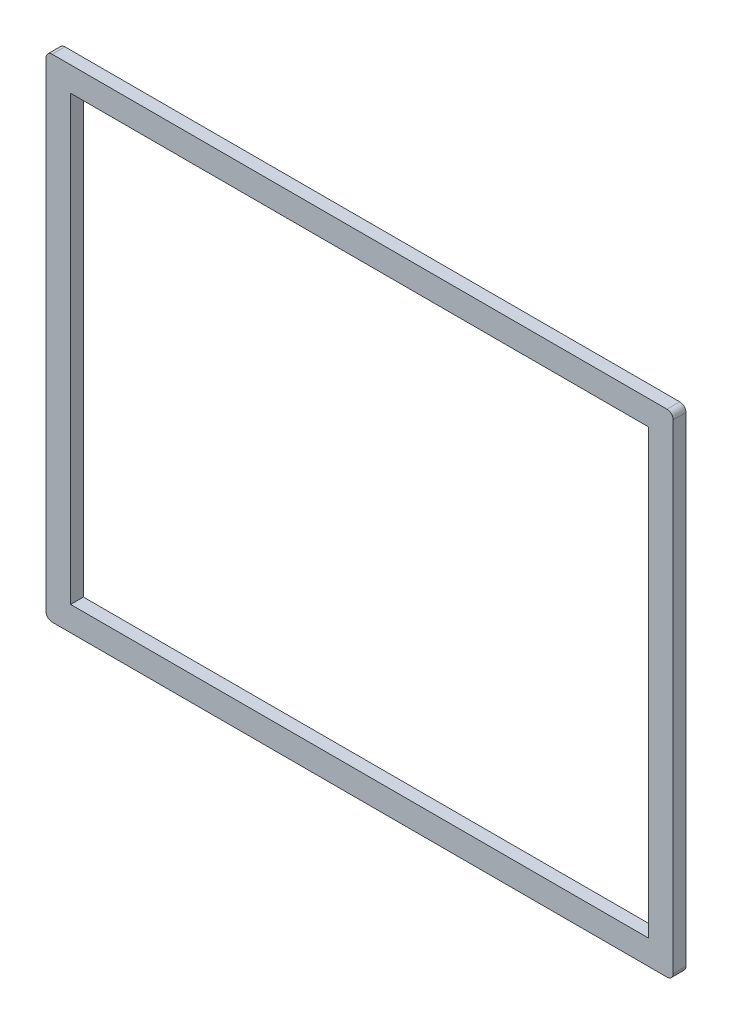
SolidWorks part; units mm, degrees
ref_plane "Front Plane" through (0, 0, 0) normal (0, 0, 1) x (1, 0, 0)
ref_plane "Top Plane" through (0, 0, 0) normal (0, 1, 0) x (1, 0, 0)
ref_plane "Right Plane" through (0, 0, 0) normal (1, 0, 0) x (0, 0, -1)
sketch "Sketch1" plane through (0, 0, 0) normal (0, 0, 1) x (1, 0, 0)
  line L0 (-298.45, -228.6) -> (298.45, 228.6) construction
  line L1 (-298.45, 228.6) -> (298.45, 228.6)
  line L2 (-298.45, 228.6) -> (-298.45, -228.6)
  line L3 (-298.45, -228.6) -> (298.45, -228.6)
  line L4 (298.45, 228.6) -> (298.45, -228.6)
  line L5 (-323.85, 254) -> (-323.85, -254)
  line L6 (-323.85, -254) -> (323.85, -254)
  line L7 (323.85, 254) -> (323.85, -254)
  line L8 (-323.85, 254) -> (323.85, 254)
  point P4 (0, 0)
  dimension "D1" = 596.9
  dimension "D2" = 457.2
  dimension "D3" = 25.4
extrude "Extrude1" add sketch "Sketch1" against normal blind 13.208
fillet "Fillet1" radius 6.35 4 edges at (-323.85, -254, -6.604) (323.85, -254, -6.604) (323.85, 254, -6.604) (-323.85, 254, -6.604)
